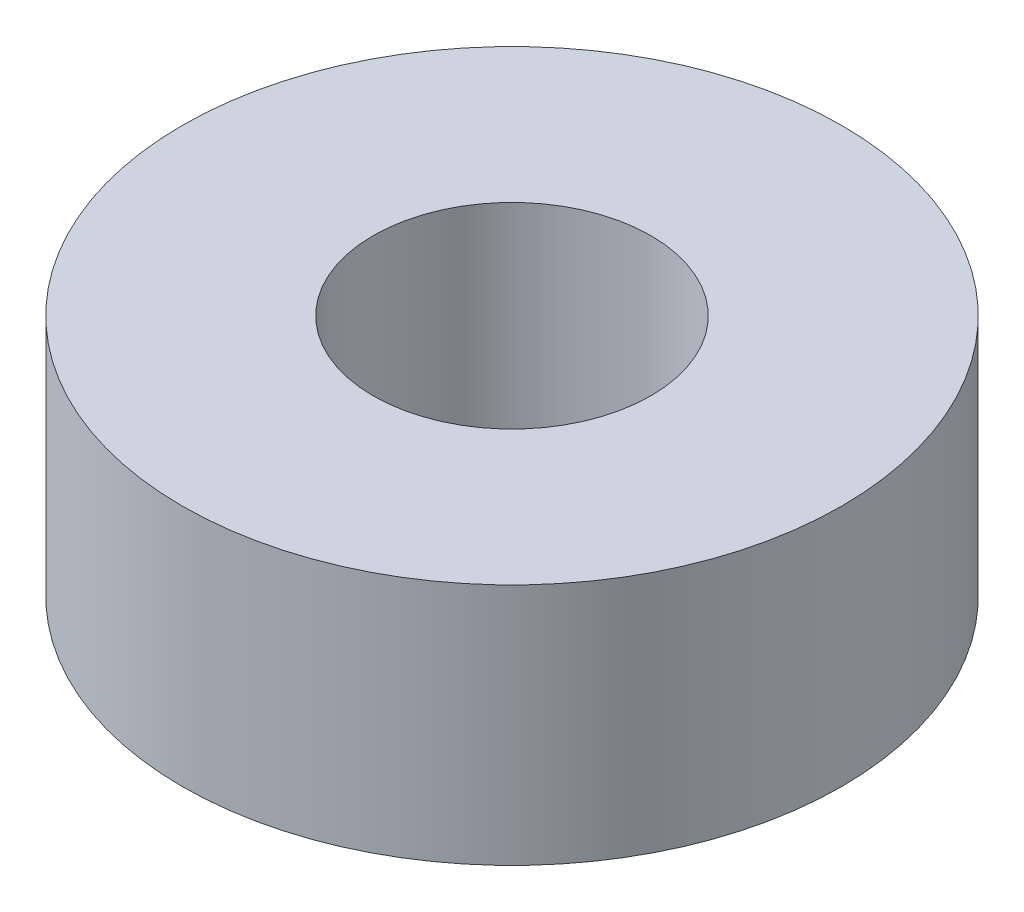
SolidWorks part; units mm, degrees
ref_plane "Front Plane" through (0, 0, 0) normal (0, 0, 1) x (1, 0, 0)
ref_plane "Top Plane" through (0, 0, 0) normal (0, 1, 0) x (1, 0, 0)
ref_plane "Right Plane" through (0, 0, 0) normal (1, 0, 0) x (0, 0, -1)
sketch "草图1" plane through (0, 0, 0) normal (0, 1, 0) x (1, 0, 0)
  circle A0 centre (0, 0) radius 4
  circle A1 centre (0, 0) radius 9.5
  dimension "D1" = 8
  dimension "D2" = 19
extrude "凸台-拉伸1" add sketch "草图1" along normal blind 7
